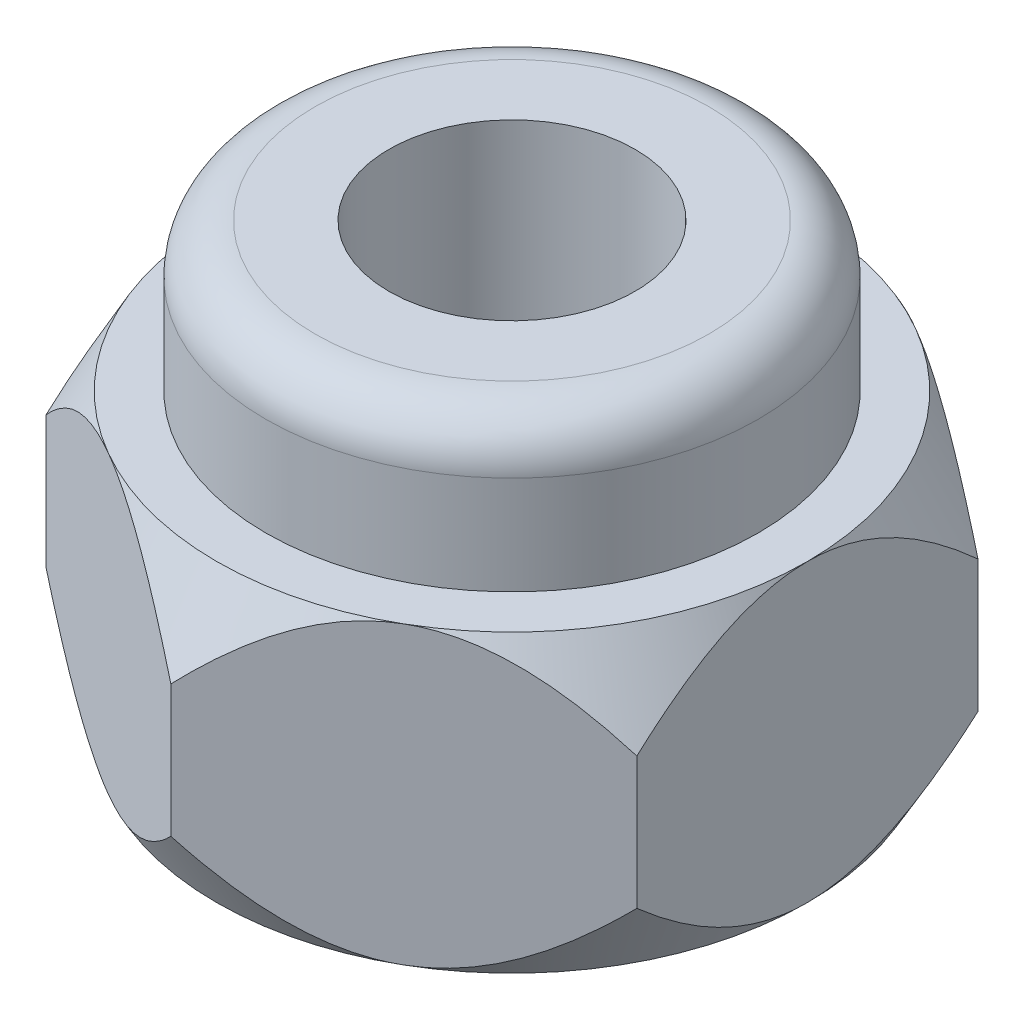
SolidWorks part; units mm, degrees
ref_plane "前视基准面" through (0, 0, 0) normal (0, 0, 1) x (1, 0, 0)
ref_plane "上视基准面" through (0, 0, 0) normal (0, 1, 0) x (1, 0, 0)
ref_plane "右视基准面" through (0, 0, 0) normal (1, 0, 0) x (0, 0, -1)
other "Configuration Table"
sketch "草图1" plane through (0, 0, 0) normal (0, 1, 0) x (1, 0, 0)
  line L1 (3, 1.7321) -> (0, 3.4641)
  line L2 (0, 3.4641) -> (-3, 1.7321)
  line L3 (-3, 1.7321) -> (-3, -1.7321)
  line L4 (-3, -1.7321) -> (0, -3.4641)
  line L5 (0, -3.4641) -> (3, -1.7321)
  line L6 (3, -1.7321) -> (3, 1.7321)
  circle A0 centre (0, 0) radius 3 construction
  dimension "D1" = 6
extrude "凸台-拉伸1" add sketch "草图1" along normal blind 3
sketch "草图2" plane through (0, 3, 0) normal (0, 1, 0) x (1, 0, 0)
  circle A0 centre (0, 0) radius 2.5
  dimension "D1" = 5
extrude "凸台-拉伸2" add sketch "草图2" along normal blind 1.5
fillet "圆角1" radius 0.5 1 edges at (0, 4.5, 2.5)
sketch "草图3" plane through (0, 0, 0) normal (0, -1, 0) x (1, 0, 0)
  circle A0 centre (0, 0) radius 1.25
  dimension "D1" = 2.5
extrude "切除-拉伸1" cut sketch "草图3" against normal through all
cosmetic thread "装饰螺纹线1" parameters "D2"=3
sketch "草图4" plane through (0, 0, 0) normal (0, 0, 1) x (1, 0, 0)
  line L0 (3.4805, 0) -> (3.4805, 0.844)
  line L1 (0, 0) -> (3, 0) construction
  line L2 (3, 3) -> (3, 0) construction
  line L3 (3.4805, 0.844) -> (3, 0)
  line L4 (3, 0) -> (3.4805, 0)
  line L5 (0, 0) -> (0, 0.8841) construction
  line L6 (0, 3) -> (0, 0) construction
  line L7 (3, 3) -> (3.4805, 3)
  line L8 (3.4805, 3) -> (3.4805, 2.1256)
  line L9 (3.4805, 2.1256) -> (3, 3)
revolve "切除-旋转1" cut sketch "草图4" angle 360 about L5
